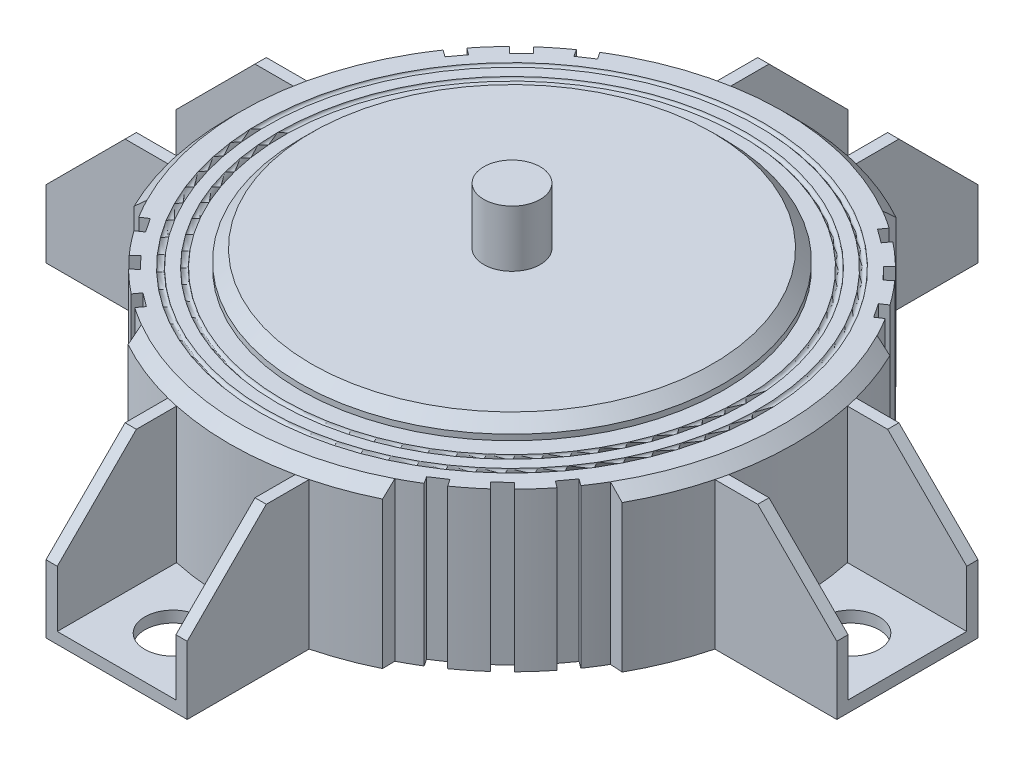
SolidWorks part; units mm, degrees
ref_plane "Front Plane" through (0, 0, 0) normal (0, 0, 1) x (1, 0, 0)
ref_plane "Top Plane" through (0, 0, 0) normal (0, 1, 0) x (1, 0, 0)
ref_plane "Right Plane" through (0, 0, 0) normal (1, 0, 0) x (0, 0, -1)
sketch "Sketch1" plane through (0, 0, 0) normal (0, 0, 1) x (1, 0, 0)
  line L0 (0, 0) -> (0, 41) construction
  line L1 (0, 0) -> (-50, 0)
  line L2 (-50, 0) -> (-50, 28)
  line L3 (-50, 28) -> (-37.5, 28)
  line L4 (-37.5, 28) -> (-37.5, 31)
  line L5 (-37.5, 31) -> (-5, 31)
  line L6 (-5, 31) -> (-5, 41)
  line L7 (-5, 41) -> (0, 41)
  line L8 (0, 0) -> (0, 41)
  dimension "D1" = 100
  dimension "D2" = 75
  dimension "D3" = 10
  dimension "D4" = 10
  dimension "D5" = 3
  dimension "D6" = 28
revolve "Revolve1" add sketch "Sketch1" angle 360 about L0
chamfer "Chamfer1" distance 2 angle 45 2 edges at (0, 28, -50) (0, 31, -37.5)
sketch "Sketch2" plane through (0, 0, 0) normal (0, 0, 1) x (1, 0, 0)
  line L0 (0, 0) -> (0, 26) construction
  line L1 (50, 26) -> (-50, 26) construction
  line L2 (-12.5, 26) -> (-12.5, 0)
  line L3 (-50, 0) -> (50, 0) construction
  line L4 (-12.5, 0) -> (12.5, 0)
  line L5 (-12.5, 26) -> (-10.5, 26)
  line L6 (-10.5, 26) -> (-10.5, 2)
  line L7 (-10.5, 2) -> (10.5, 2)
  line L8 (10.5, 26) -> (10.5, 2)
  line L9 (12.5, 26) -> (10.5, 26)
  line L10 (12.5, 26) -> (12.5, 0)
  point P14 (0, 2)
  dimension "D1" = 2
  dimension "D2" = 2
  dimension "D3" = 25
extrude "Boss-Extrude1" add sketch "Sketch2" along normal blind 70
chamfer "Chamfer2" distance 14 angle 45 2 edges at (-11.5, 26, 70) (11.5, 26, 70)
sketch "Sketch3" plane through (0, 0, 0) normal (0, 1, 0) x (1, 0, 0)
  line L0 (0, -60) -> (0, 0) construction
  circle A0 centre (0, -60) radius 5
  dimension "D2" = 10
  dimension "D1" = 60
extrude "Cut-Extrude1" cut sketch "Sketch3" along normal blind 70
pattern_circular "CirPattern1" count 4 over 360 about axis through (0, 0, 0) along (0, 1, 0) of "Cut-Extrude1", "Chamfer2", "Boss-Extrude1"
sketch "Sketch4" plane through (0, 0, 0) normal (0, 1, 0) x (1, 0, 0)
  line L0 (0, 0) -> (34.4487, -36.2393) construction
  line L1 (21.9512, -42.6866) -> (21.9901, -44.9047)
  line L2 (41.5204, -24.0843) -> (43.7337, -24.2355)
  arc A0 (12.5, -48.4123) -> (48.4123, -12.5) centre (0, 0) ccw construction
  circle A1 centre (0, 0) radius 48 construction
  arc A2 (21.9901, -44.9047) -> (43.7337, -24.2355) centre (0, 0) ccw
  arc A3 (21.9512, -42.6866) -> (41.5204, -24.0843) centre (0, 0) ccw
  dimension "D1" = 30
  dimension "D2" = 27
extrude "Cut-Extrude2" cut sketch "Sketch4" along normal blind 70
sketch "Sketch5" plane through (0, 0, 0) normal (0, 1, 0) x (1, 0, 0)
  line L0 (0, 0) -> (33.0707, -34.7898)
  line L1 (33.017, -36.9104) -> (35.1914, -34.8435)
  line L2 (33.017, -36.9104) -> (30.9501, -34.736)
  line L3 (35.1914, -34.8435) -> (33.1244, -32.6691)
  line L4 (30.9501, -34.736) -> (33.1244, -32.6691)
  line L5 (34.1579, -33.7563) -> (31.9835, -35.8232)
  line L6 (34.1042, -35.8769) -> (32.0373, -33.7026) construction
  arc A0 (21.9512, -42.6866) -> (41.5204, -24.0843) centre (0, 0) ccw construction
  point P6 (0, 0)
  dimension "D1" = 3
  dimension "D2" = 3
extrude "Cut-Extrude3" cut sketch "Sketch5" along normal blind 70 contours L1 L3 L4 L2
pattern_circular "CirPattern2" count 2 every 10 about axis through (0, 0, 0) along (0, 1, 0) of "Cut-Extrude3"
pattern_circular "CirPattern3" count 4 over 360 about axis through (0, 0, 0) along (0, 1, 0) of "CirPattern2", "Cut-Extrude3", "Cut-Extrude2"
sketch "Sketch6" plane through (0, 28, 0) normal (0, 1, 0) x (1, 0, 0)
  circle A0 centre (0, 0) radius 41
  dimension "D1" = 82
sketch "Sketch7" plane through (0, 28, 0) normal (0, 1, 0) x (1, 0, 0)
  circle A0 centre (0, 0) radius 44
  dimension "D1" = 88
sweep "Cut-Sweep1" cut path "Sketch6" circular profile diameter 1 parameters "D3"=1
sweep "Cut-Sweep2" cut path "Sketch7" circular profile diameter 1 parameters "D3"=1
sketch "Sketch16" plane through (0, 0, 0) normal (0, -1, 0) x (1, 0, 0)
  circle A0 centre (0, 0) radius 37.5
  dimension "D1" = 75
extrude "Cut-Extrude4" cut sketch "Sketch16" against normal blind 10
